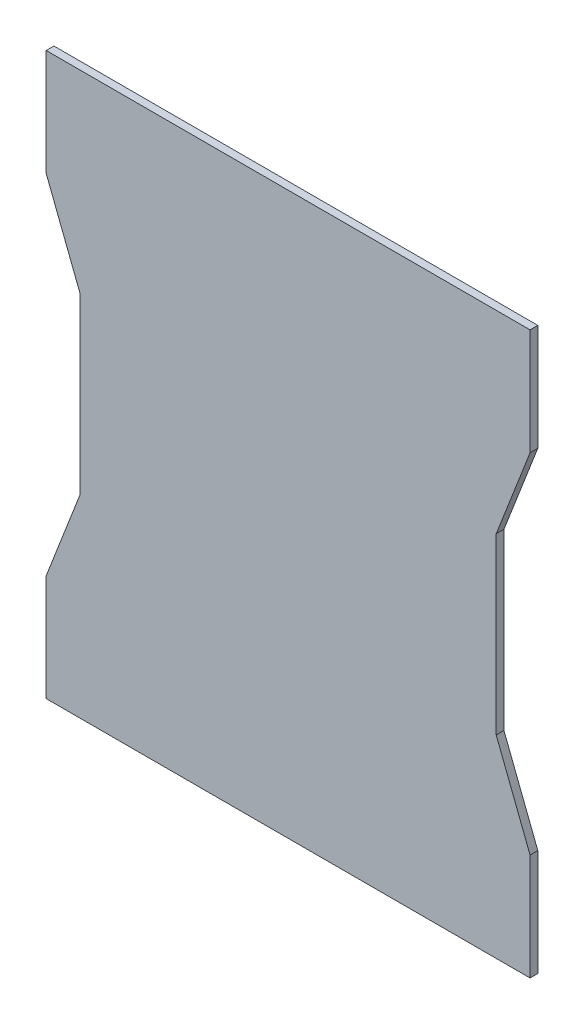
SolidWorks part; units mm, degrees
ref_plane "前视基准面" through (0, 0, 0) normal (0, 0, 1) x (1, 0, 0)
ref_plane "上视基准面" through (0, 0, 0) normal (0, 1, 0) x (1, 0, 0)
ref_plane "右视基准面" through (0, 0, 0) normal (1, 0, 0) x (0, 0, -1)
sketch "草图2" plane through (0, 0, 0) normal (0, 0, 1) x (1, 0, 0)
  line L1 (-500, 580) -> (500, 580)
  line L2 (-500, 580) -> (-500, -580)
  line L3 (-500, -580) -> (500, -580)
  line L4 (500, 580) -> (500, -580)
  dimension "D1" = 1000
  dimension "D2" = 1160
  dimension "D3" = 500
  dimension "D4" = 580
extrude "凸台-拉伸1" add sketch "草图2" along normal blind 16
sketch "草图4" plane through (0, 0, 0) normal (0, 0, -1) x (-1, 0, 0)
  line L0 (-500, -580) -> (-500, 580) construction
  line L1 (-500, 360) -> (-430, 180)
  line L2 (-430, 180) -> (-430, -180)
  line L3 (-430, -180) -> (-500, -360)
  line L4 (-500, -360) -> (-500, 360)
  line L5 (430, 180) -> (430, -180)
  line L6 (430, -180) -> (500, -360)
  line L7 (500, 580) -> (500, -580) construction
  line L8 (500, -360) -> (500, 360)
  line L9 (500, 360) -> (430, 180)
  line L10 (-500, 580) -> (500, 580) construction
  line L11 (500, -580) -> (-500, -580) construction
  dimension "D1" = 70
  dimension "D2" = 70
  dimension "D3" = 220
  dimension "D4" = 180
  dimension "D5" = 220
  dimension "D6" = 180
extrude "切除-拉伸1" cut sketch "草图4" against normal through all
